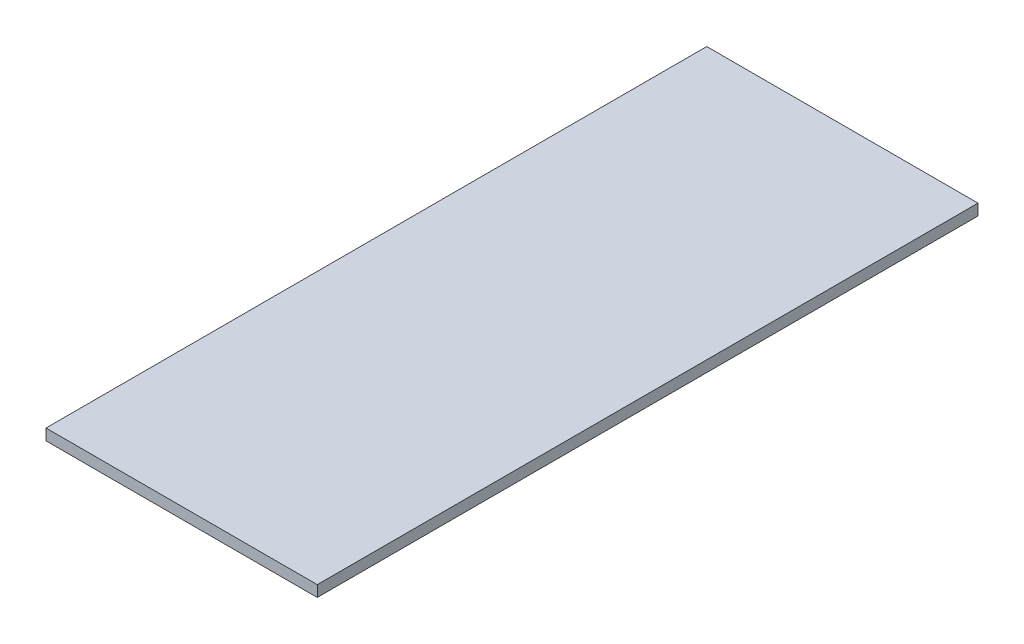
SolidWorks part; units mm, degrees
ref_plane "前视基准面" through (0, 0, 0) normal (0, 0, 1) x (1, 0, 0)
ref_plane "上视基准面" through (0, 0, 0) normal (0, 1, 0) x (1, 0, 0)
ref_plane "右视基准面" through (0, 0, 0) normal (1, 0, 0) x (0, 0, -1)
other "Configuration Table"
sketch "草图1" plane through (0, 0, 0) normal (0, 1, 0) x (1, 0, 0)
  line L1 (0, 0) -> (39, 0)
  line L2 (0, 0) -> (0, 95)
  line L3 (0, 95) -> (39, 95)
  line L4 (39, 0) -> (39, 95)
  dimension "D1" = 95
  dimension "D2" = 39
extrude "凸台-拉伸1" add sketch "草图1" along normal blind 1.6
